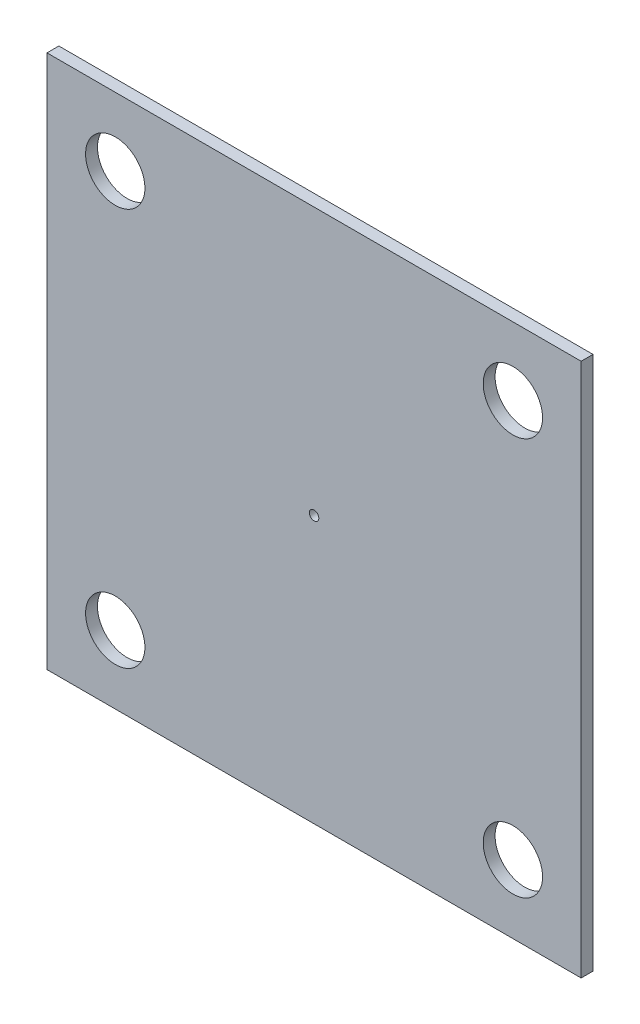
SolidWorks part; units mm, degrees
ref_plane "Front Plane" through (0, 0, 0) normal (0, 0, 1) x (1, 0, 0)
ref_plane "Top Plane" through (0, 0, 0) normal (0, 1, 0) x (1, 0, 0)
ref_plane "Right Plane" through (0, 0, 0) normal (1, 0, 0) x (0, 0, -1)
sketch "Sketch1" plane through (0, 0, 0) normal (0, 0, 1) x (1, 0, 0)
  line L1 (-225, 225) -> (225, 225)
  line L2 (-225, 225) -> (-225, -225)
  line L3 (-225, -225) -> (225, -225)
  line L4 (225, 225) -> (225, -225)
  line L5 (-225, 225) -> (225, -225) construction
  line L6 (-225, -225) -> (225, 225) construction
  line L15 (-192.5, 192.5) -> (192.5, 192.5) construction
  line L16 (-192.5, 192.5) -> (-192.5, -192.5) construction
  line L17 (-192.5, -192.5) -> (192.5, -192.5) construction
  line L18 (192.5, 192.5) -> (192.5, -192.5) construction
  line L19 (-192.5, 192.5) -> (192.5, -192.5) construction
  line L20 (-192.5, -192.5) -> (192.5, 192.5) construction
  circle A0 centre (0, 0) radius 4
  circle A1 centre (1000, 0) radius 1000 construction
  circle A2 centre (-167.5, -167.5) radius 25
  circle A3 centre (167.5, -167.5) radius 25
  circle A4 centre (167.5, 167.5) radius 25
  circle A5 centre (-167.5, 167.5) radius 25
  point P20 (750, 0)
  point P49 (822.7486, 0)
  dimension "D1" = 8
  dimension "D2" = 2000
  dimension "D8" = 50
  dimension "D3" = 450
  dimension "D4" = 450
  dimension "D6" = 385
  dimension "D7" = 385
extrude "Boss-Extrude1" add sketch "Sketch1" along normal mid plane 10
